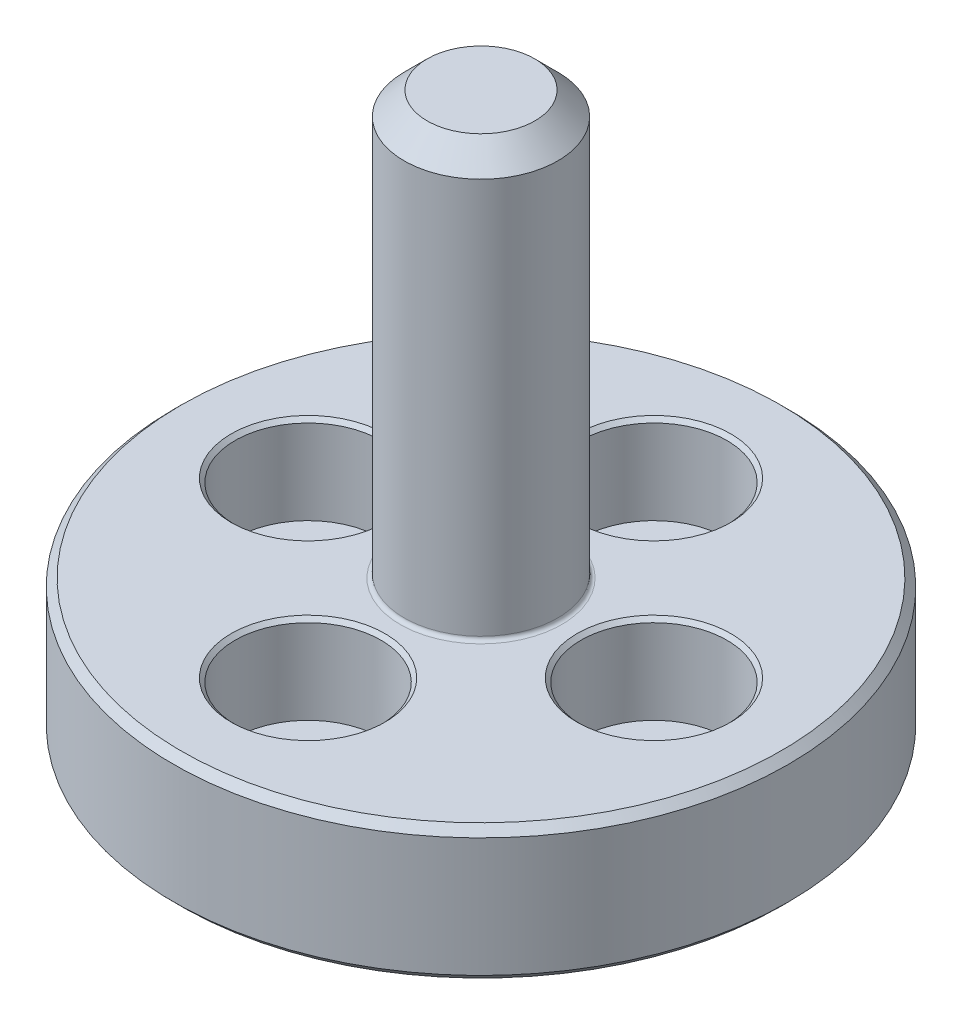
SolidWorks part; units mm, degrees
material "1060 Legierung"
ref_plane "Ebene vorne" through (0, 0, 0) normal (0, 0, 1) x (1, 0, 0)
ref_plane "Ebene oben" through (0, 0, 0) normal (0, 1, 0) x (1, 0, 0)
ref_plane "Ebene rechts" through (0, 0, 0) normal (1, 0, 0) x (0, 0, -1)
sketch "Skizze2" plane through (0, 0, 0) normal (0, 0, 1) x (1, 0, 0)
  line L0 (0, 0) -> (8, 0)
  line L1 (8, 0) -> (8, 3.5)
  line L2 (8, 3.5) -> (2, 3.5)
  line L3 (2, 3.5) -> (2, 14.5)
  line L4 (2, 14.5) -> (0, 14.5)
  line L5 (0, 0) -> (0, 14.5)
  line L6 (0, 0) -> (0, 14.5) construction
  dimension "D1" = 14.5
  dimension "D2" = 4
  dimension "D3" = 16
  dimension "D4" = 3.5
revolve "Rotation1" add sketch "Skizze2" angle 360 about L6
sketch "Skizze3" plane through (0, 3.5, 0) normal (0, 1, 0) x (1, 0, 0)
  circle A0 centre (0, 4.5) radius 1.05
  dimension "D1" = 2.1
  dimension "D2" = 4.5
extrude "Schnitt-Linear austragen1" cut sketch "Skizze3" against normal through all
sketch "Skizze4" plane through (0, 3.5, 0) normal (0, 1, 0) x (1, 0, 0)
  circle A0 centre (0, 4.5) radius 1.9
  dimension "D1" = 3.8
extrude "Schnitt-Linear austragen2" cut sketch "Skizze4" against normal blind 2.3
chamfer "Fase1" distance 0.1 angle 45 2 edges at (-1.05, 0, -4.5) (-1.9, 3.5, -4.5)
pattern_circular "Kreismuster1" count 4 over 360 about axis through (0, 0, 0) along (0, 1, 0) of "Schnitt-Linear austragen2", "Schnitt-Linear austragen1", "Fase1"
fillet "Verrundung1" radius 0.1 1 edges at (2, 3.5, 0)
chamfer "Fase2" distance 0.6 angle 45 1 edges at (2, 14.5, 0)
sketch "Skizze5" plane through (0, 0, 0) normal (0, -1, 0) x (1, 0, 0)
  circle A0 centre (0, 0) radius 1
  dimension "D1" = 2
extrude "Schnitt-Linear austragen3" cut sketch "Skizze5" against normal blind 4.5
chamfer "Fase3" distance 0.2 angle 45 3 edges at (8, 3.5, 0) (1, 0, 0) (8, 0, 0)
